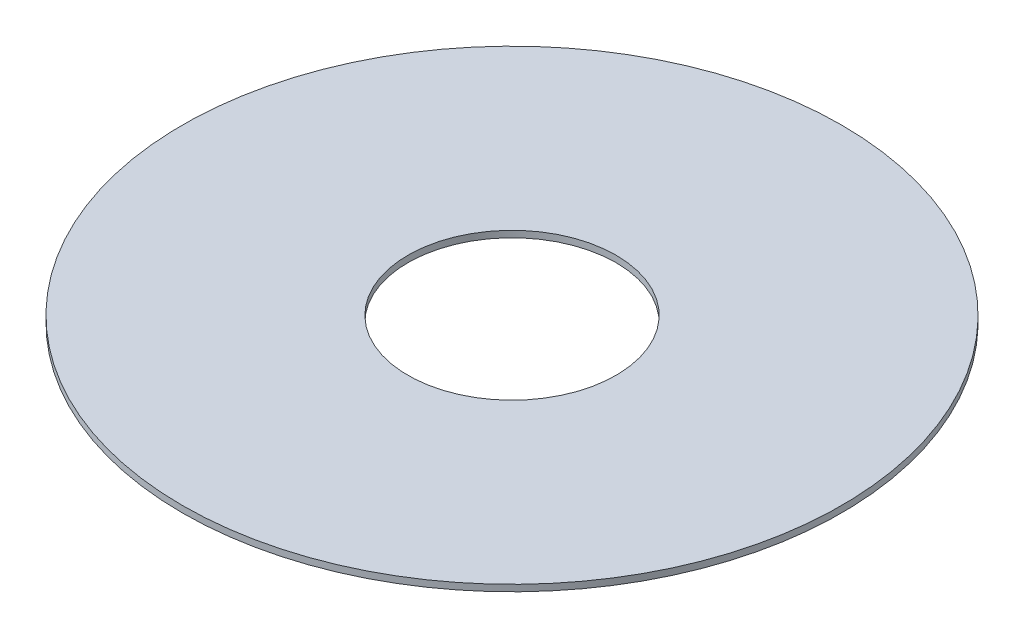
SolidWorks part; units mm, degrees
material "PC High Viscosity"
ref_plane "Front Plane" through (0, 0, 0) normal (0, 0, 1) x (1, 0, 0)
ref_plane "Top Plane" through (0, 0, 0) normal (0, 1, 0) x (1, 0, 0)
ref_plane "Right Plane" through (0, 0, 0) normal (1, 0, 0) x (0, 0, -1)
sketch "Sketch1" plane through (0, 0, 0) normal (0, 1, 0) x (1, 0, 0)
  circle A0 centre (0, 0) radius 241.3
  circle A1 centre (0, 0) radius 76.2
  dimension "D1" = 482.6
  dimension "D2" = 152.4
extrude "Boss-Extrude1" add sketch "Sketch1" along normal blind 4.7625
